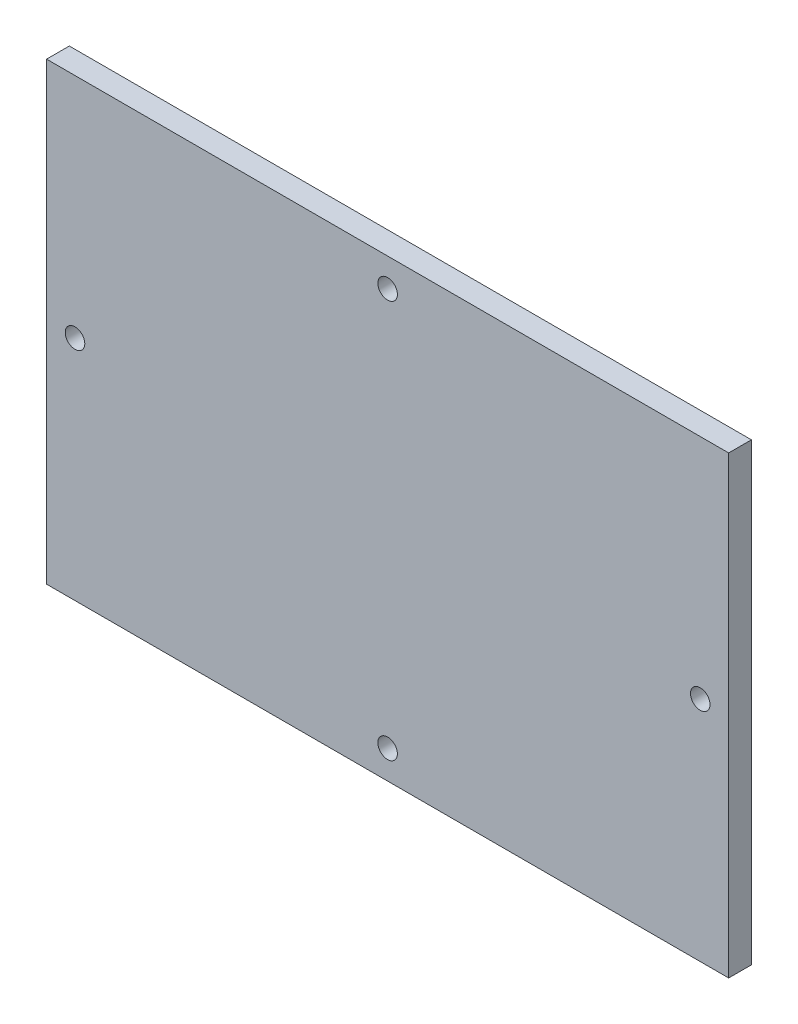
SolidWorks part; units mm, degrees
ref_plane "Front Plane" through (0, 0, 0) normal (0, 0, 1) x (1, 0, 0)
ref_plane "Top Plane" through (0, 0, 0) normal (0, 1, 0) x (1, 0, 0)
ref_plane "Right Plane" through (0, 0, 0) normal (1, 0, 0) x (0, 0, -1)
sketch "Sketch2" plane through (0, 0, 0) normal (0, 0, 1) x (1, 0, 0)
  line L1 (38.1, -25.4) -> (-38.1, -25.4)
  line L2 (38.1, -25.4) -> (38.1, 25.4)
  line L3 (38.1, 25.4) -> (-38.1, 25.4)
  line L4 (-38.1, -25.4) -> (-38.1, 25.4)
  line L5 (38.1, -25.4) -> (-38.1, 25.4) construction
  line L6 (38.1, 25.4) -> (-38.1, -25.4) construction
  point P0 (0, 0)
  dimension "D1" = 76.2
  dimension "D2" = 50.8
extrude "Boss-Extrude1" add sketch "Sketch2" along normal blind 2.54
sketch "Sketch3" plane through (0, 0, 2.54) normal (0, 0, 1) x (1, 0, 0)
  line L6 (0, -19.05) -> (0, -22.225) construction
  circle A0 centre (-34.925, 0) radius 1.0922
  circle A1 centre (34.925, 0) radius 1.0922
  circle A2 centre (0, -22.225) radius 1.0922
  circle A3 centre (0, 22.225) radius 1.0922
  point P12 (0, 0)
  point P21 (-31.75, 0)
  dimension "D4" = 2.1844
  dimension "D6" = 2.1844
extrude "Cut-Extrude1" cut sketch "Sketch3" against normal blind 2.54
